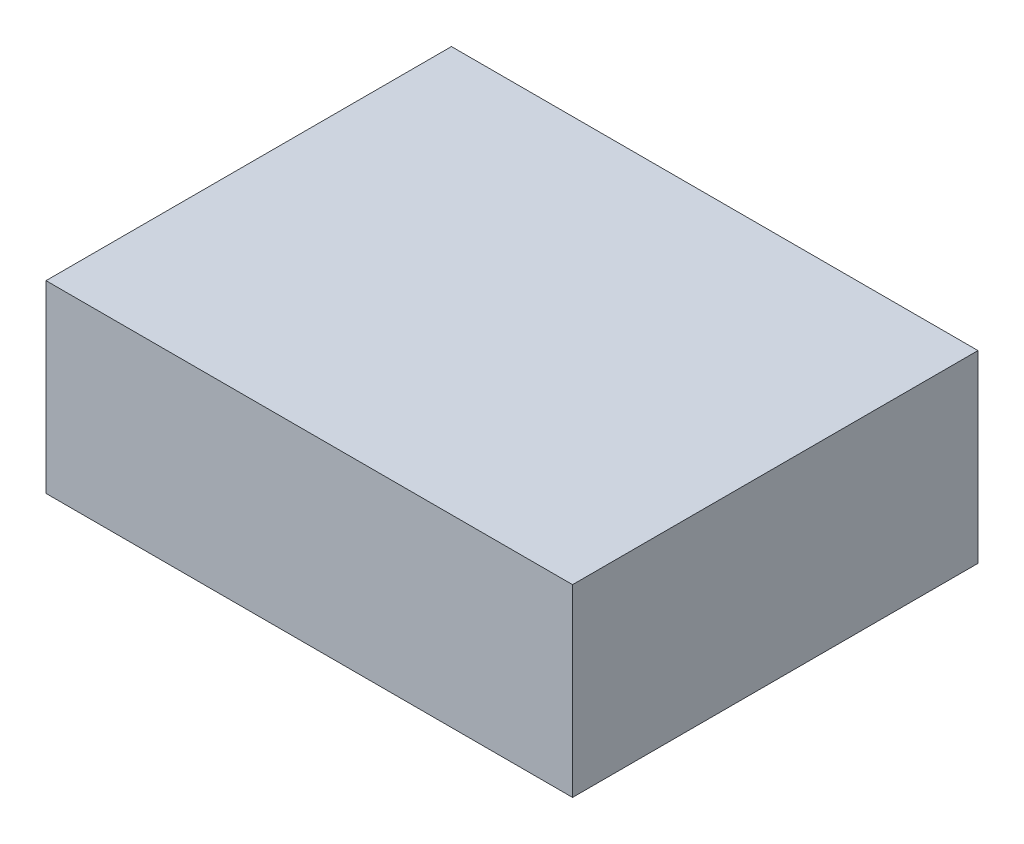
SolidWorks part; units mm, degrees
ref_plane "Front Plane" through (0, 0, 0) normal (0, 0, 1) x (1, 0, 0)
ref_plane "Top Plane" through (0, 0, 0) normal (0, 1, 0) x (1, 0, 0)
ref_plane "Right Plane" through (0, 0, 0) normal (1, 0, 0) x (0, 0, -1)
sketch "Sketch1" plane through (0, 0, 0) normal (0, 1, 0) x (1, 0, 0)
  line L1 (0, 0) -> (50.8, 0)
  line L2 (0, 0) -> (0, 39.116)
  line L3 (0, 39.116) -> (50.8, 39.116)
  line L4 (50.8, 0) -> (50.8, 39.116)
  dimension "D1" = 39.116
  dimension "D2" = 50.8
extrude "Boss-Extrude1" add sketch "Sketch1" along normal blind 17.78
